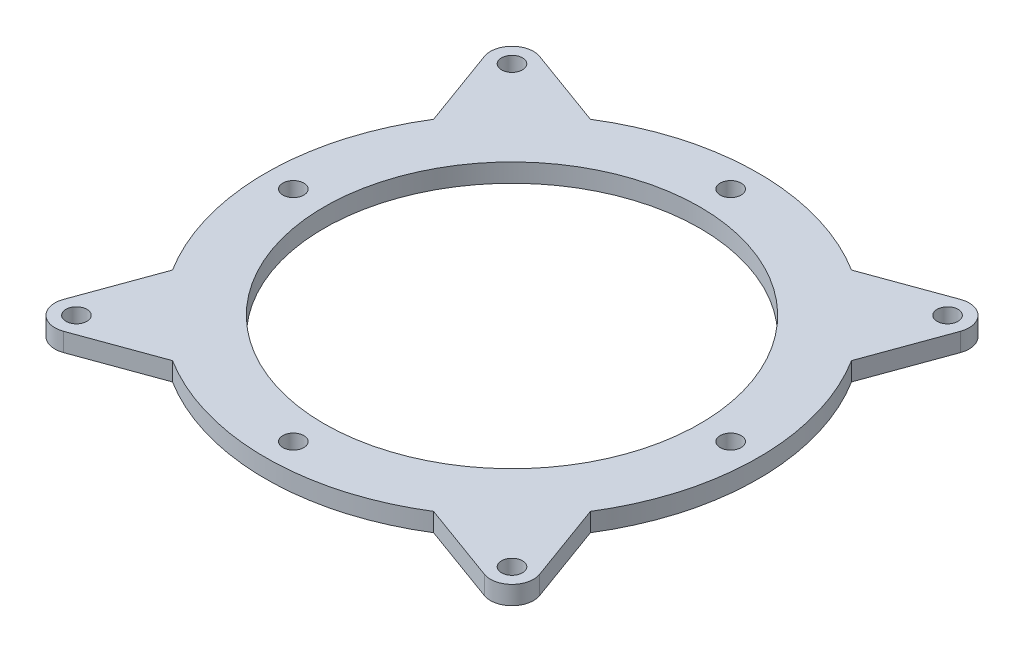
SolidWorks part; units mm, degrees
ref_plane "前视基准面" through (0, 0, 0) normal (0, 0, 1) x (1, 0, 0)
ref_plane "上视基准面" through (0, 0, 0) normal (0, 1, 0) x (1, 0, 0)
ref_plane "右视基准面" through (0, 0, 0) normal (1, 0, 0) x (0, 0, -1)
sketch "草图1" plane through (0, 0, 0) normal (0, 1, 0) x (1, 0, 0)
  line L0 (0, 35.5) -> (0, 0) construction
  line L1 (0, 0) -> (35.5, 0) construction
  line L2 (34.1583, 38.6443) -> (21.192, 33.9249)
  line L3 (-35.3553, -35.3553) -> (35.3553, 35.3553) construction
  line L4 (38.6443, 34.1583) -> (33.9249, 21.192)
  line L5 (34.1583, -38.6443) -> (21.192, -33.9249)
  line L6 (38.6443, -34.1583) -> (33.9249, -21.192)
  line L7 (-38.6443, -34.1583) -> (-33.9249, -21.192)
  line L8 (-34.1583, -38.6443) -> (-21.192, -33.9249)
  line L9 (-34.1583, 38.6443) -> (-21.192, 33.9249)
  line L10 (-38.6443, 34.1583) -> (-33.9249, 21.192)
  circle A0 centre (0, 0) radius 30.5
  arc A1 (-21.192, -33.9249) -> (21.192, -33.9249) centre (0, 0) ccw
  circle A2 centre (0, 0) radius 35.5 construction
  circle A3 centre (0, 35.5) radius 1.7
  circle A4 centre (35.5, 0) radius 1.7
  circle A5 centre (0, -35.5) radius 1.7
  circle A6 centre (-35.5, 0) radius 1.7
  circle A7 centre (35.3553, 35.3553) radius 1.7
  arc A8 (38.6443, 34.1583) -> (34.1583, 38.6443) centre (35.3553, 35.3553) ccw
  arc A9 (34.1583, -38.6443) -> (38.6443, -34.1583) centre (35.3553, -35.3553) ccw
  circle A10 centre (35.3553, -35.3553) radius 1.7
  arc A11 (-38.6443, -34.1583) -> (-34.1583, -38.6443) centre (-35.3553, -35.3553) ccw
  circle A12 centre (-35.3553, -35.3553) radius 1.7
  arc A13 (-34.1583, 38.6443) -> (-38.6443, 34.1583) centre (-35.3553, 35.3553) ccw
  circle A14 centre (-35.3553, 35.3553) radius 1.7
  circle A15 centre (0, 0) radius 40 construction
  arc A16 (33.9249, -21.192) -> (33.9249, 21.192) centre (0, 0) ccw
  arc A17 (21.192, 33.9249) -> (-21.192, 33.9249) centre (0, 0) ccw
  arc A18 (-33.9249, 21.192) -> (-33.9249, -21.192) centre (0, 0) ccw
  point P18 (0, 0)
  point P21 (62.0088, -39.0875)
  point P24 (0, 0)
  point P47 (0, 0)
  dimension "D1" = 4.5
  dimension "D2" = 80
  dimension "D3" = 5
  dimension "D4" = 3.4
  dimension "D8" = 100
  dimension "D9" = 25
  dimension "D10" = 3.4
  dimension "D7" = 7
  dimension "D6" = 45
  dimension "D5" = 4
  dimension "D11" = 4
extrude "凸台-拉伸1" add sketch "草图1" along normal blind 3
